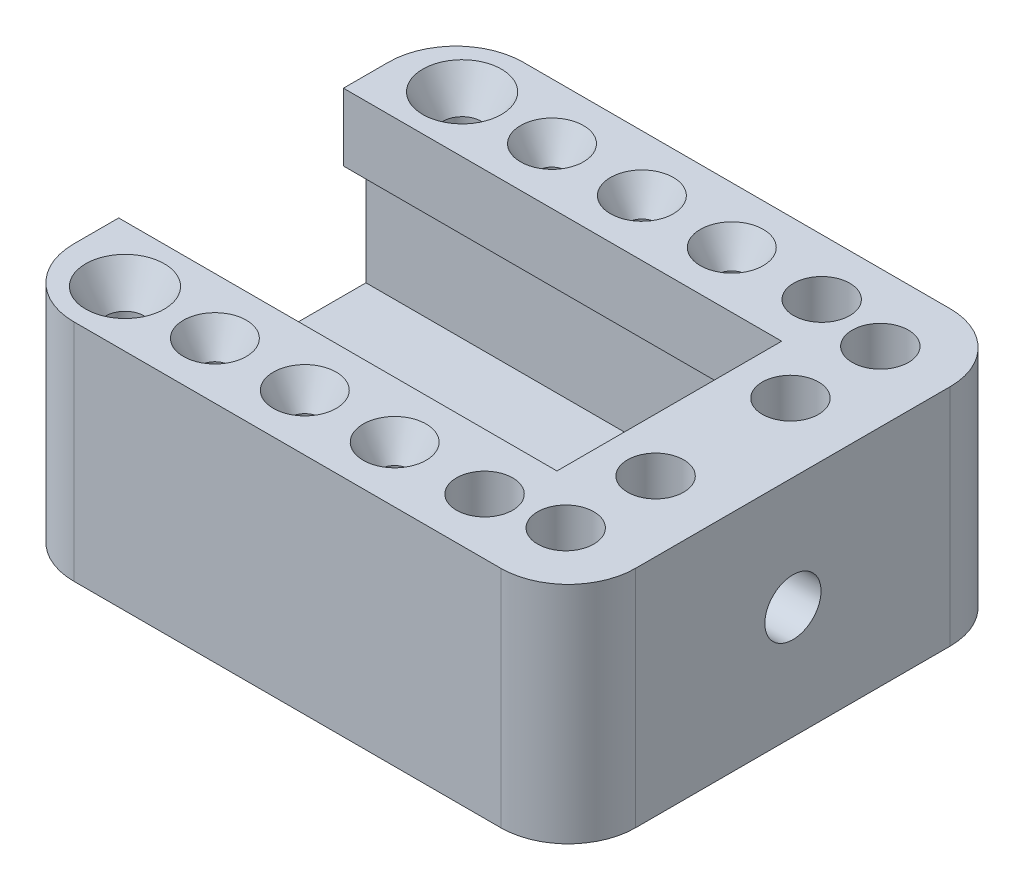
SolidWorks part; units mm, degrees
material "PVC 0.007 Plasticized"
ref_plane "Front Plane" through (0, 0, 0) normal (0, 0, 1) x (1, 0, 0)
ref_plane "Top Plane" through (0, 0, 0) normal (0, 1, 0) x (1, 0, 0)
ref_plane "Right Plane" through (0, 0, 0) normal (1, 0, 0) x (0, 0, -1)
other "Configuration Table"
sketch "Sketch1" plane through (0, 0, 0) normal (0, 1, 0) x (1, 0, 0)
  line L1 (0, 0) -> (63.5, 0)
  line L2 (0, 0) -> (0, 50.8)
  line L3 (0, 50.8) -> (63.5, 50.8)
  line L4 (63.5, 0) -> (63.5, 50.8)
  dimension "D1" = 63.5
  dimension "D2" = 50.8
extrude "Boss-Extrude1" add sketch "Sketch1" along normal blind 25.4
fillet "Fillet1" radius 7.62 4 edges at (0, 12.7, -50.8) (63.5, 12.7, -50.8) (0, 12.7, 0) (63.5, 12.7, 0)
sketch "Sketch2" plane through (0, 0, 0) normal (-1, 0, 0) x (0, 0, 1)
  line L0 (-38.1, 24.003) -> (-12.7, 24.003)
  line L5 (-50.8, 0) -> (-50.8, 25.4) construction
  line L6 (-40.64, 17.78) -> (-38.1, 17.78)
  line L7 (-40.64, 17.78) -> (-40.64, 5.08)
  line L8 (-40.64, 5.08) -> (-10.16, 5.08)
  line L9 (-10.16, 17.78) -> (-10.16, 5.08)
  line L10 (0, 25.4) -> (0, 0) construction
  line L11 (-43.18, 0) -> (-7.62, 0) construction
  line L12 (-38.1, 17.78) -> (-38.1, 24.003)
  line L14 (-12.7, 17.78) -> (-10.16, 17.78)
  line L15 (-12.7, 24.003) -> (-12.7, 17.78)
  line L16 (-43.18, 25.4) -> (-7.62, 25.4) construction
  dimension "D1" = 10.16
  dimension "D2" = 10.16
  dimension "D3" = 12.7
  dimension "D4" = 5.08
  dimension "D5" = 2.54
  dimension "D6" = 2.54
  dimension "D7" = 1.397
extrude "Cut-Extrude1" cut sketch "Sketch2" against normal blind 50.8
sketch "Sketch4" plane through (0, 25.4, 0) normal (0, 1, 0) x (1, 0, 0)
  line L0 (0, 12.7) -> (49.53, 12.7)
  line L2 (50.8, 12.7) -> (0, 12.7) construction
  line L4 (49.53, 12.7) -> (49.53, 38.1)
  line L5 (50.8, 38.1) -> (0, 38.1) construction
  line L6 (49.53, 38.1) -> (0, 38.1)
  line L7 (0, 38.1) -> (0, 12.7)
  line L8 (50.8, 12.7) -> (50.8, 38.1) construction
  dimension "D1" = 1.27
extrude "Cut-Extrude2" cut sketch "Sketch4" against normal blind 13.462
hole_wizard "CSK for #2 Flat Head Machine Screw (100)1" positions "Sketch5" profile "Sketch6" countersink size "#2" standard "ANSI Inch" end condition through all
sketch "Sketch5" plane through (0, 25.4, 0) normal (0, 1, 0) x (1, 0, 0)
  line L0 (49.53, 38.1) -> (0, 38.1) construction
  point P0 (7.0612, 44.45)
  dimension "D1" = 6.35
sketch "Sketch6" plane through (7.0612, 25.4, -44.45) normal (1, 0, 0) x (0, 0, 1)
  line L0 (0, 0) -> (0, 25.4)
  line L1 (0, 25.4) -> (2.159, 25.4)
  line L2 (2.159, 25.4) -> (2.159, 3.9595)
  line L3 (2.159, 3.9595) -> (4.445, 0)
  line L5 (4.445, 0) -> (0, 0)
  line L6 (-2.159, 3.9595) -> (-4.445, 0) construction
  line L11 (0, -6.35) -> (0, 107.95) construction
  dimension "Thru Hole Dia." = 4.318
  dimension "Thru Hole Depth" = 25.4
  dimension "Near C'Sink Dia." = 8.89
  dimension "Near C'Sink Angle" = 60
hole_wizard "CSK for #2 Flat Head Machine Screw (100)2" positions "Sketch7" profile "Sketch8" countersink size "#2" standard "ANSI Inch" end condition through all
sketch "Sketch7" plane through (0, 25.4, 0) normal (0, 1, 0) x (1, 0, 0)
  line L0 (49.53, 38.1) -> (0, 38.1) construction
  circle A0 centre (7.0612, 44.45) radius 2.159 construction
  point P0 (17.2212, 44.45)
  point P2 (27.3812, 44.45)
  point P4 (37.5412, 44.45)
  dimension "D1" = 10.16
  dimension "D2" = 10.16
  dimension "D3" = 10.16
  dimension "D4" = 6.35
sketch "Sketch8" plane through (17.2212, 25.4, -44.45) normal (1, 0, 0) x (0, 0, 1)
  line L0 (0, 0) -> (0, 25.4)
  line L1 (0, 25.4) -> (1.5875, 25.4)
  line L2 (1.5875, 25.4) -> (1.5875, 3.4095)
  line L3 (1.5875, 3.4095) -> (3.556, 0)
  line L5 (3.556, 0) -> (0, 0)
  line L6 (-1.5875, 3.4095) -> (-3.556, 0) construction
  line L11 (0, -6.35) -> (0, 107.95) construction
  dimension "Thru Hole Dia." = 3.175
  dimension "Thru Hole Depth" = 25.4
  dimension "Near C'Sink Dia." = 7.112
  dimension "Near C'Sink Angle" = 60
sketch "Sketch9" plane through (0, 25.4, 0) normal (0, 1, 0) x (1, 0, 0)
  line L0 (49.53, 38.1) -> (0, 38.1) construction
  circle A0 centre (47.7012, 44.45) radius 3.175
  circle A1 centre (37.5412, 44.45) radius 3.556 construction
  dimension "D1" = 6.35
  dimension "D2" = 10.16
  dimension "D3" = 6.35
extrude "Cut-Extrude3" cut sketch "Sketch9" against normal blind 12.7
hole_wizard "1/4 (0.25) Diameter Hole1" positions "Sketch10" profile "Sketch11" hole size "1/4" standard "ANSI Inch" end condition through all
sketch "Sketch10" plane through (0, 25.4, 0) normal (0, 1, 0) x (1, 0, 0)
  line L1 (49.53, 38.1) -> (0, 38.1) construction
  line L3 (63.5, 7.62) -> (63.5, 43.18) construction
  point P0 (55.6006, 43.18)
  dimension "D2" = 7.8994
  dimension "D1" = 5.08
sketch "Sketch11" plane through (55.6006, 25.4, -43.18) normal (1, 0, 0) x (0, 0, 1)
  line L0 (0, 0) -> (0, 25.4)
  line L1 (0, 25.4) -> (3.175, 25.4)
  line L2 (3.175, 25.4) -> (3.175, 0)
  line L5 (3.175, 0) -> (0, 0)
  line L11 (0, -6.35) -> (0, 107.95) construction
  dimension "Thru Hole Dia." = 6.35
  dimension "Thru Hole Depth" = 25.4
ref_plane "Plane1" through (0, 0, -25.4) normal (0, 0, 1) x (1, 0, 0)
mirror "Mirror1" about plane through (0, 0, -25.4) normal (0, 0, 1) of "Cut-Extrude3", "1/4 (0.25) Diameter Hole1", "CSK for #2 Flat Head Machine Screw (100)2", "CSK for #2 Flat Head Machine Screw (100)1"
hole_wizard "1/4 (0.25) Diameter Hole2" positions "Sketch12" profile "Sketch13" hole size "1/4" standard "ANSI Inch" end condition through all
sketch "Sketch12" plane through (0, 25.4, 0) normal (0, 1, 0) x (1, 0, 0)
  line L0 (49.53, 12.7) -> (49.53, 38.1) construction
  line L2 (55.6006, 43.18) -> (55.6006, 7.62) construction
  point P3 (55.6006, 33.02)
  point P5 (55.6006, 17.78)
  dimension "D3" = 10.16
  dimension "D1" = 6.0706
  dimension "D2" = 10.16
sketch "Sketch13" plane through (55.6006, 25.4, -33.02) normal (1, 0, 0) x (0, 0, 1)
  line L0 (0, 0) -> (0, 25.4)
  line L1 (0, 25.4) -> (3.175, 25.4)
  line L2 (3.175, 25.4) -> (3.175, 0)
  line L5 (3.175, 0) -> (0, 0)
  line L11 (0, -6.35) -> (0, 107.95) construction
  dimension "Thru Hole Dia." = 6.35
  dimension "Thru Hole Depth" = 25.4
sketch "Sketch14" plane through (0, 0, 0) normal (0, -1, 0) x (1, 0, 0)
  line L1 (9.9977, -8.7357) -> (10.5955, -4.9997)
  line L2 (10.5955, -4.9997) -> (7.659, -2.614)
  line L3 (7.659, -2.614) -> (4.1247, -3.9643)
  line L4 (4.1247, -3.9643) -> (3.5269, -7.7003)
  line L5 (3.5269, -7.7003) -> (6.4634, -10.086)
  line L6 (6.4634, -10.086) -> (9.9977, -8.7357)
  line L12 (6.4634, -10.086) -> (6.4634, -52.4419) construction
  line L13 (7.659, -40.714) -> (4.1247, -42.0643)
  line L14 (4.1247, -42.0643) -> (3.5269, -45.8003)
  line L15 (3.5269, -45.8003) -> (6.4634, -48.186)
  line L16 (6.4634, -48.186) -> (9.9977, -46.8357)
  line L17 (9.9977, -46.8357) -> (10.5955, -43.0997)
  line L18 (10.5955, -43.0997) -> (7.659, -40.714)
  circle A0 centre (7.0612, -6.35) radius 3.2766 construction
  circle A2 centre (7.0612, -44.45) radius 3.2766 construction
  dimension "D1" = 6.5532
  dimension "D2" = 6.5532
extrude "Cut-Extrude4" cut sketch "Sketch14" against normal blind 2.54
sketch "Sketch15" plane through (0, 0, 0) normal (0, -1, 0) x (1, 0, 0)
  line L0 (63.5, -25.4) -> (0, -25.4) construction
  line L5 (63.5, -7.62) -> (63.5, -43.18) construction
  line L6 (0, -43.18) -> (0, -7.62) construction
  line L8 (41.1792, -29.1151) -> (44.2751, -29.1151)
  line L9 (41.1792, -29.1151) -> (41.1792, -21.6849)
  line L10 (41.1792, -21.6849) -> (44.2751, -21.6849)
  line L11 (44.2751, -29.1151) -> (44.2751, -21.6849)
  line L12 (41.1792, -29.1151) -> (44.2751, -21.6849) construction
  line L13 (41.1792, -21.6849) -> (44.2751, -29.1151) construction
  line L14 (39.2234, -29.1151) -> (31.7933, -29.1151)
  line L15 (39.2234, -29.1151) -> (39.2234, -21.6849)
  line L16 (39.2234, -21.6849) -> (31.7933, -21.6849)
  line L17 (31.7933, -29.1151) -> (31.7933, -21.6849)
  line L18 (39.2234, -29.1151) -> (31.7933, -21.6849) construction
  line L19 (39.2234, -21.6849) -> (31.7933, -29.1151) construction
  line L20 (29.8254, -29.1151) -> (29.8254, -21.6849)
  line L21 (29.8254, -29.1151) -> (22.3953, -29.1151)
  line L22 (22.3953, -29.1151) -> (22.3953, -21.6849)
  line L23 (29.8254, -21.6849) -> (22.3953, -21.6849)
  line L24 (20.4274, -29.1151) -> (20.4274, -21.6849)
  line L25 (20.4274, -29.1151) -> (12.9973, -29.1151)
  line L26 (12.9973, -29.1151) -> (12.9973, -21.6849)
  line L27 (20.4274, -21.6849) -> (12.9973, -21.6849)
  line L28 (41.1792, -12.1256) -> (44.2751, -12.1256)
  line L29 (20.4274, -19.7291) -> (12.9973, -19.7291)
  line L30 (44.2751, -19.5558) -> (44.2751, -12.1256)
  line L31 (39.2234, -12.1256) -> (31.7933, -19.5558) construction
  line L32 (39.2234, -12.1256) -> (31.7933, -12.1256)
  line L33 (29.8254, -19.5558) -> (22.3953, -19.5558)
  line L34 (31.7933, -19.5558) -> (31.7933, -12.1256)
  line L35 (39.2234, -19.5558) -> (39.2234, -12.1256)
  line L36 (39.2234, -19.5558) -> (31.7933, -12.1256) construction
  line L37 (22.3953, -19.5558) -> (22.3953, -12.1256)
  line L38 (12.9973, -19.7291) -> (12.9973, -12.299)
  line L39 (39.2234, -19.5558) -> (31.7933, -19.5558)
  line L40 (20.4274, -19.7291) -> (20.4274, -12.299)
  line L41 (41.1792, -19.5558) -> (44.2751, -12.1256) construction
  line L42 (41.1792, -19.5558) -> (41.1792, -12.1256)
  line L43 (29.8254, -12.1256) -> (22.3953, -12.1256)
  line L44 (29.8254, -19.5558) -> (29.8254, -12.1256)
  line L45 (41.1792, -12.1256) -> (44.2751, -19.5558) construction
  line L46 (41.1792, -19.5558) -> (44.2751, -19.5558)
  line L47 (20.4274, -12.299) -> (12.9973, -12.299)
  line L48 (39.2234, -38.501) -> (31.7933, -38.501)
  line L49 (39.2234, -31.0709) -> (31.7933, -38.501) construction
  line L50 (41.1792, -31.0709) -> (44.0973, -31.0709)
  line L51 (39.2234, -38.501) -> (31.7933, -31.0709) construction
  line L52 (29.8254, -38.6788) -> (29.8254, -31.0709)
  line L53 (22.3953, -38.6788) -> (22.3953, -31.0709)
  line L54 (20.4274, -31.0709) -> (12.9973, -31.0709)
  line L55 (41.1792, -31.0709) -> (44.0973, -38.6788) construction
  line L56 (44.0973, -38.6788) -> (44.0973, -31.0709)
  line L57 (20.4274, -38.501) -> (12.9973, -38.501)
  line L58 (39.2234, -38.501) -> (39.2234, -31.0709)
  line L59 (39.2234, -31.0709) -> (31.7933, -31.0709)
  line L60 (29.8254, -38.6788) -> (22.3953, -38.6788)
  line L61 (20.4274, -38.501) -> (20.4274, -31.0709)
  line L62 (41.1792, -38.6788) -> (44.0973, -38.6788)
  line L63 (12.9973, -38.501) -> (12.9973, -31.0709)
  line L64 (41.1792, -38.6788) -> (44.0973, -31.0709) construction
  line L65 (31.7933, -38.501) -> (31.7933, -31.0709)
  line L66 (41.1792, -38.6788) -> (41.1792, -31.0709)
  line L67 (29.8254, -31.0709) -> (22.3953, -31.0709)
  point P6 (42.7272, -25.4)
  point P11 (35.5084, -25.4)
  point P16 (42.7272, -15.8407)
  point P29 (35.5084, -15.8407)
  point P42 (42.6383, -34.8748)
  point P47 (35.5084, -34.7859)
  dimension "D1" = 1.9558
  dimension "D2" = 3
  dimension "D3" = 1.9558
  dimension "D4" = 1.9558
extrude "Cut-Extrude5" cut sketch "Sketch15" against normal blind 2.54
sketch "Sketch16" plane through (63.5, 0, 0) normal (1, 0, 0) x (0, 0, -1)
  line L0 (25.4, 25.4) -> (25.4, 0) construction
  line L1 (7.62, 25.4) -> (43.18, 25.4) construction
  line L2 (7.62, 0) -> (43.18, 0) construction
  line L3 (0, 12.7) -> (50.8, 12.7) construction
  line L4 (0, 0) -> (0, 25.4) construction
  line L5 (50.8, 25.4) -> (50.8, 0) construction
  circle A0 centre (25.4, 12.7) radius 3.175
  dimension "D1" = 6.35
extrude "Cut-Extrude8" cut sketch "Sketch16" against normal blind 6.985
sketch "Sketch17" plane through (50.8, 0, 0) normal (-1, 0, 0) x (0, 0, 1)
  circle A0 centre (-25.4, 12.7) radius 3.81
  dimension "D1" = 7.62
extrude "Cut-Extrude9" cut sketch "Sketch17" against normal blind 6.985
